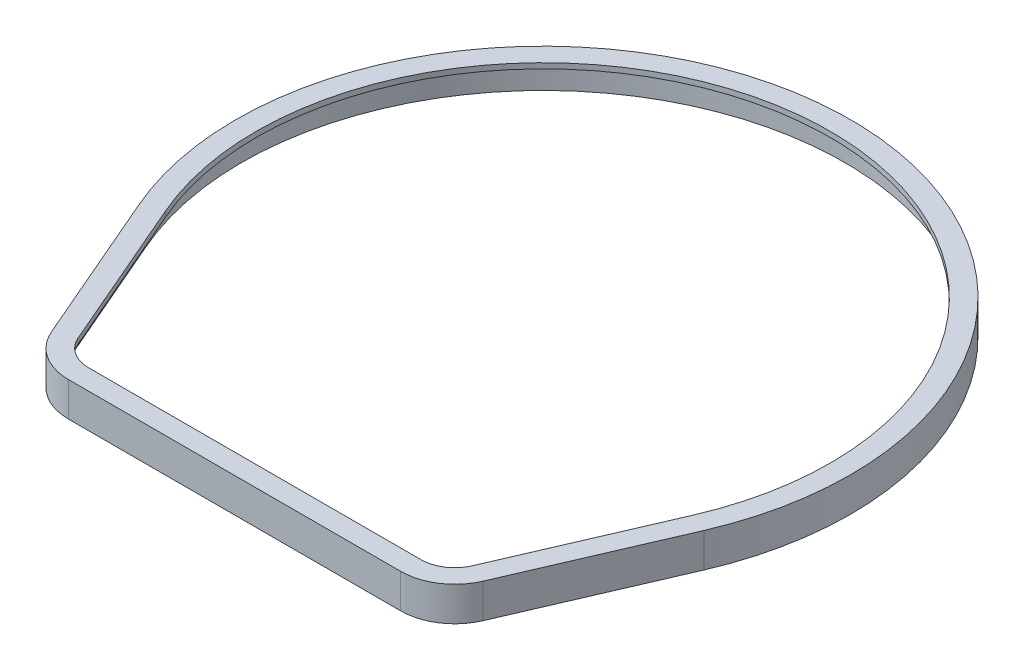
SolidWorks part; units mm, degrees
ref_plane "Front Plane" through (0, 0, 0) normal (0, 0, 1) x (1, 0, 0)
ref_plane "Top Plane" through (0, 0, 0) normal (0, 1, 0) x (1, 0, 0)
ref_plane "Right Plane" through (0, 0, 0) normal (1, 0, 0) x (0, 0, -1)
sketch "Sketch1" plane through (0, 0, 0) normal (0, 1, 0) x (1, 0, 0)
  line L0 (-34.4227, -62.75) -> (34.4227, -62.75)
  line L1 (43.605, -56.7106) -> (57.389, -24.7538)
  line L2 (0, 0) -> (0, -62.75) construction
  line L3 (0, 0) -> (57.389, -24.7538) construction
  line L4 (-43.605, -56.7106) -> (-57.389, -24.7538)
  line L5 (44.7069, -57.1859) -> (58.4909, -25.2291)
  line L6 (-34.4227, -63.95) -> (34.4227, -63.95)
  line L7 (-44.7069, -57.1859) -> (-58.4909, -25.2291)
  circle A0 centre (0, 0) radius 62.5
  arc A1 (34.4227, -62.75) -> (43.605, -56.7106) centre (34.4227, -52.75) ccw
  arc A2 (-43.605, -56.7106) -> (-34.4227, -62.75) centre (-34.4227, -52.75) ccw
  arc A3 (34.4227, -63.95) -> (44.7069, -57.1859) centre (34.4227, -52.75) ccw
  arc A4 (-44.7069, -57.1859) -> (-34.4227, -63.95) centre (-34.4227, -52.75) ccw
  arc A6 (58.4909, -25.2291) -> (-58.4909, -25.2291) centre (0, 0) ccw
  point P10 (41, -62.75)
  point P13 (-41, -62.75)
  dimension "D1" = 125
  dimension "D4" = 10
  dimension "D2" = 41
  dimension "D3" = 90
  dimension "D6" = 62.75
  dimension "D5" = 1.2
extrude "Boss-Extrude1" add sketch "Sketch1" along normal blind 6 contours L5 A6 L7 A4 L6 A3 A2 L4 A0 L1 A1 L0
sketch "Sketch3" plane through (0, 6, 0) normal (0, 1, 0) x (1, 0, 0)
  line L14 (-58.4909, -25.2291) -> (-44.7069, -57.1859)
  line L15 (44.7069, -57.1859) -> (58.4909, -25.2291)
  line L16 (-34.4227, -63.95) -> (34.4227, -63.95)
  line L17 (-58.4909, -25.2291) -> (-44.7069, -57.1859)
  line L18 (44.7069, -57.1859) -> (58.4909, -25.2291)
  line L19 (-34.4227, -63.95) -> (34.4227, -63.95)
  line L30 (40.8503, -55.5224) -> (54.6344, -23.5656)
  line L31 (-34.4227, -59.75) -> (34.4227, -59.75)
  line L32 (-54.6344, -23.5656) -> (-40.8503, -55.5224)
  line L33 (40.8503, -55.5224) -> (54.6344, -23.5656)
  line L34 (-34.4227, -59.75) -> (34.4227, -59.75)
  line L35 (-54.6344, -23.5656) -> (-40.8503, -55.5224)
  arc A13 (58.4909, -25.2291) -> (-58.4909, -25.2291) centre (0, 0) ccw
  arc A14 (34.4227, -63.95) -> (44.7069, -57.1859) centre (34.4227, -52.75) ccw
  arc A15 (-44.7069, -57.1859) -> (-34.4227, -63.95) centre (-34.4227, -52.75) ccw
  arc A16 (58.4909, -25.2291) -> (-58.4909, -25.2291) centre (0, 0) ccw
  arc A17 (34.4227, -63.95) -> (44.7069, -57.1859) centre (34.4227, -52.75) ccw
  arc A18 (-44.7069, -57.1859) -> (-34.4227, -63.95) centre (-34.4227, -52.75) ccw
  arc A30 (34.4227, -59.75) -> (40.8503, -55.5224) centre (34.4227, -52.75) ccw
  arc A31 (-40.8503, -55.5224) -> (-34.4227, -59.75) centre (-34.4227, -52.75) ccw
  arc A32 (54.6344, -23.5656) -> (-54.6344, -23.5656) centre (0, 0) ccw
  arc A33 (34.4227, -59.75) -> (40.8503, -55.5224) centre (34.4227, -52.75) ccw
  arc A34 (-40.8503, -55.5224) -> (-34.4227, -59.75) centre (-34.4227, -52.75) ccw
  arc A35 (54.6344, -23.5656) -> (-54.6344, -23.5656) centre (0, 0) ccw
  dimension "D1" = 0
  dimension "D2" = 3
extrude "Boss-Extrude2" add sketch "Sketch3" along normal blind 1.1
